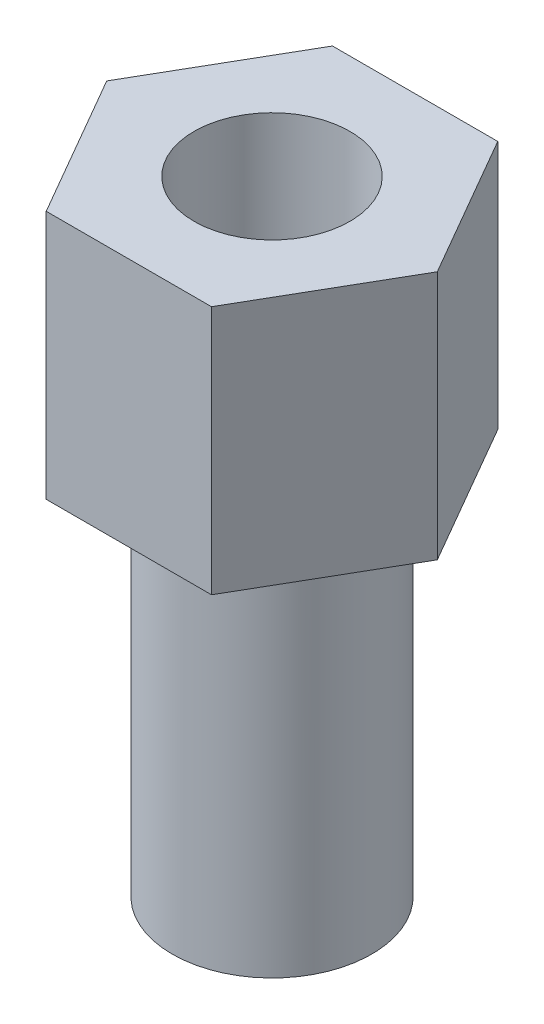
SolidWorks part; units mm, degrees
ref_plane "前视基准面" through (0, 0, 0) normal (0, 0, 1) x (1, 0, 0)
ref_plane "上视基准面" through (0, 0, 0) normal (0, 1, 0) x (1, 0, 0)
ref_plane "右视基准面" through (0, 0, 0) normal (1, 0, 0) x (0, 0, -1)
sketch "草图4" plane through (0, 0, 0) normal (0, 1, 0) x (1, 0, 0)
  line L0 (-12.7945, 0) -> (16.3015, 0) construction
  line L2 (1.325, -2.295) -> (2.65, 0)
  line L3 (2.65, 0) -> (1.325, 2.295)
  line L4 (1.325, 2.295) -> (-1.325, 2.295)
  line L5 (-1.325, 2.295) -> (-2.65, 0)
  line L6 (-2.65, 0) -> (-1.325, -2.295)
  line L7 (-1.325, -2.295) -> (1.325, -2.295)
  circle A0 centre (0, 0) radius 2.295 construction
  dimension "D1" = 5.3
extrude "凸台-拉伸1" add sketch "草图4" along normal blind 4
sketch "草图6" plane through (0, 0, 0) normal (0, -1, 0) x (-1, 0, 0)
  circle A0 centre (0, 0) radius 1.6
  dimension "D1" = 3.2
extrude "凸台-拉伸2" add sketch "草图6" along normal blind 6
cosmetic thread "装饰螺纹线1"
sketch "草图7" plane through (0, 4, 0) normal (0, 1, 0) x (1, 0, 0)
  circle A0 centre (0, 0) radius 1.25
  dimension "D1" = 2.5
extrude "切除-拉伸1" cut sketch "草图7" against normal blind 5
cosmetic thread "装饰螺纹线2" parameters "D2"=3
